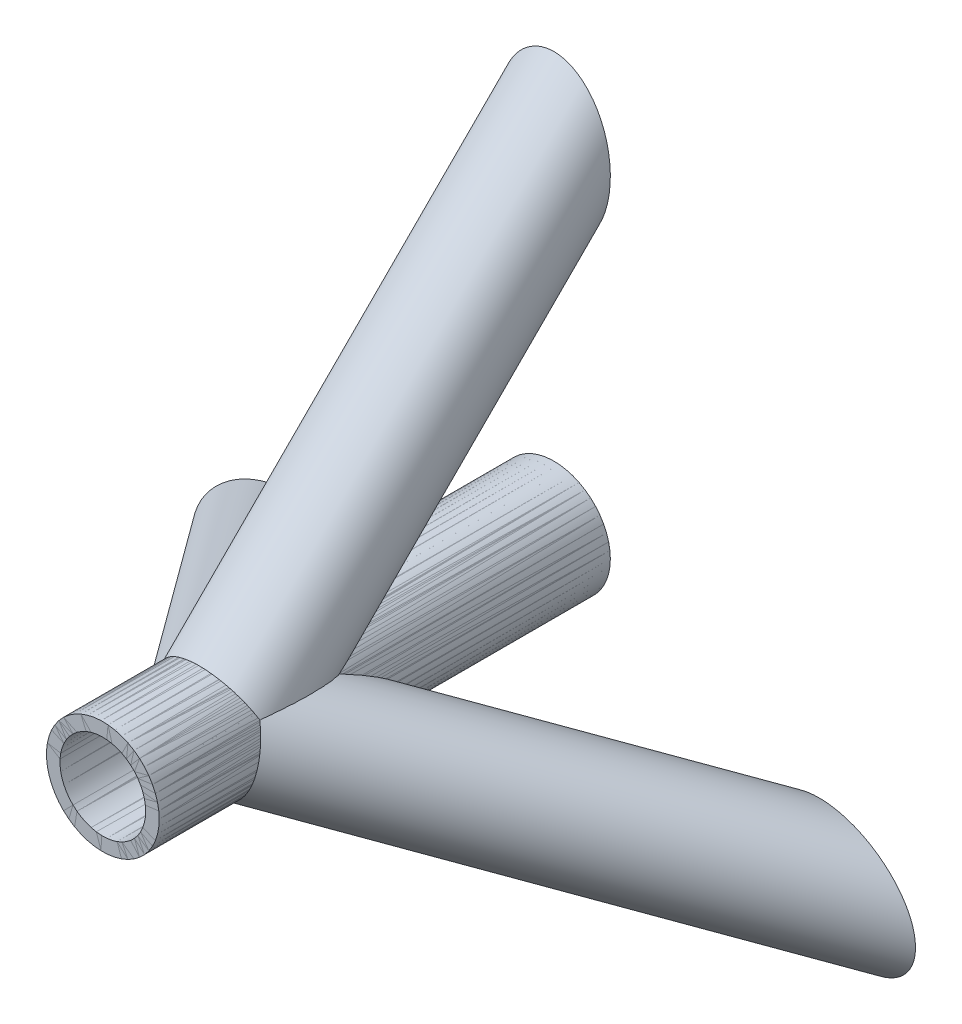
SolidWorks part; units mm, degrees
ref_plane "Plan de face" through (0, 0, 0) normal (0, 0, 1) x (1, 0, 0)
ref_plane "Plan de dessus" through (0, 0, 0) normal (0, 1, 0) x (1, 0, 0)
ref_plane "Plan de droite" through (0, 0, 0) normal (1, 0, 0) x (0, 0, -1)
sketch "Esquisse1" plane through (0, 0, 0) normal (0, 0, 1) x (1, 0, 0)
  line L0 (0, 0) -> (59.7743, 0) construction
  line L1 (0, 0) -> (-29.8872, -51.7661) construction
  line L2 (0, 0) -> (-29.8872, 51.7661) construction
  circle A0 centre (0, 0) radius 9.5
  circle A1 centre (0, 0) radius 12.5
  point P9 (0, 0)
  dimension "D1" = 3
  dimension "D2" = 19
  dimension "D3" = 25
extrude "Boss.-Extru.1" add sketch "Esquisse1" along normal blind 100
ref_plane "Plan1" through (0, 0, 0) normal (0, -0.7071, 0.7071) x (1, 0, 0)
sketch "Esquisse5" plane through (0, 0, 0) normal (0, -0.7071, 0.7071) x (1, 0, 0)
  circle A0 centre (0, 51.9323) radius 9.5
  circle A1 centre (0, 51.9323) radius 12.5
  dimension "D1" = 19
  dimension "D2" = 25
extrude "Boss.-Extru.3" add sketch "Esquisse5" along normal up to next and the other way up to surface other way up to plane "Plan de face"
pattern_circular "Répétition circulaire2" count 3 over 360 about axis through (0, 0, 0) along (0, 0, 1) of bodies 104
